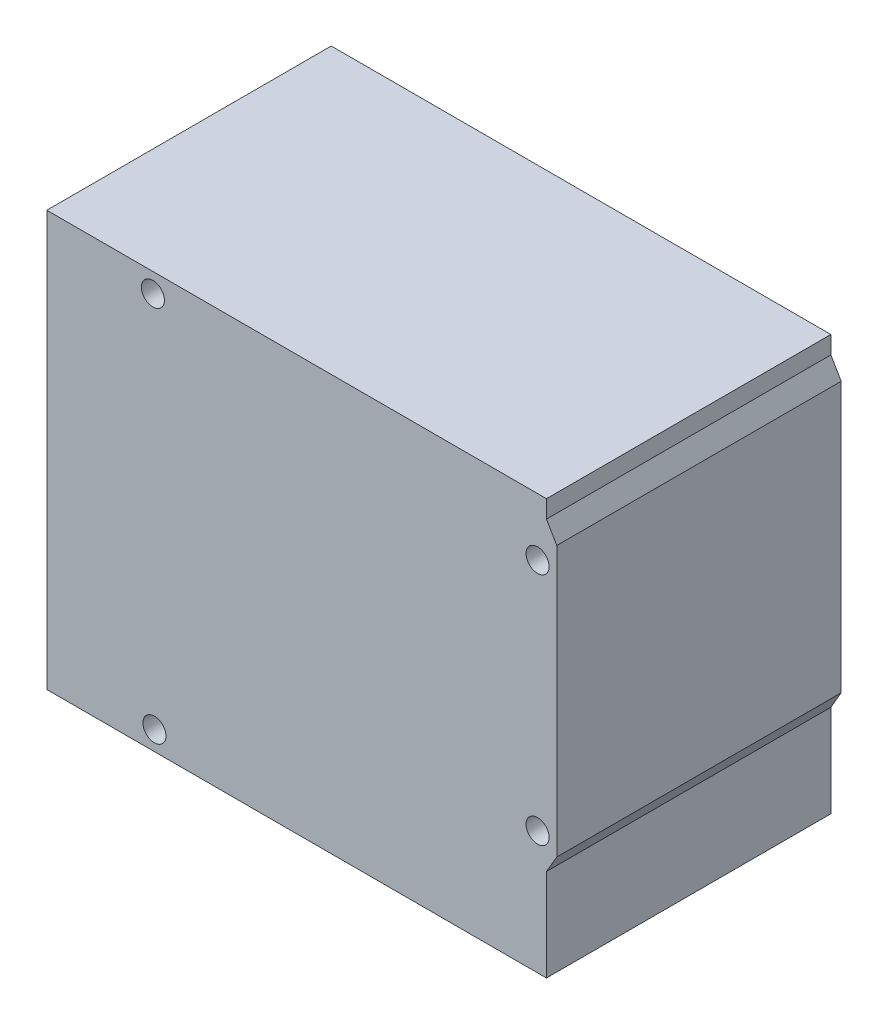
SolidWorks part; units mm, degrees
ref_plane "Front Plane" through (0, 0, 0) normal (0, 0, 1) x (1, 0, 0)
ref_plane "Top Plane" through (0, 0, 0) normal (0, 1, 0) x (1, 0, 0)
ref_plane "Right Plane" through (0, 0, 0) normal (1, 0, 0) x (0, 0, -1)
sketch "Sketch1" plane through (0, 0, 0) normal (0, 0, 1) x (1, 0, 0)
  line L0 (0, 0) -> (0, 54)
  line L1 (0, 54) -> (65, 54)
  line L2 (65, 54) -> (65, 51.7)
  line L3 (65, 51.7) -> (66.3413, 49.4)
  line L4 (66.3413, 49.4) -> (66.3413, 14.3)
  line L5 (66.3413, 14.3) -> (65, 12)
  line L6 (65, 12) -> (65, 0)
  line L7 (65, 0) -> (0, 0)
  circle A0 centre (13.8, 51.5) radius 1.5
  circle A1 centre (63.8413, 46.5) radius 1.5
  circle A2 centre (63.8413, 16) radius 1.5
  circle A3 centre (14, 2.5) radius 1.5
  dimension "D7" = 3
  dimension "D8" = 13.8
  dimension "D9" = 2.5
  dimension "D10" = 2.5
  dimension "D11" = 14
  dimension "D12" = 7.5
  dimension "D15" = 16
  dimension "D1" = 54
  dimension "D2" = 2.3
  dimension "D3" = 12
  dimension "D4" = 2.3
  dimension "D5" = 2.3
  dimension "D6" = 65
  dimension "D13" = 2.5
  dimension "D14" = 2.5
extrude "Boss-Extrude1" add sketch "Sketch1" along normal blind 37
